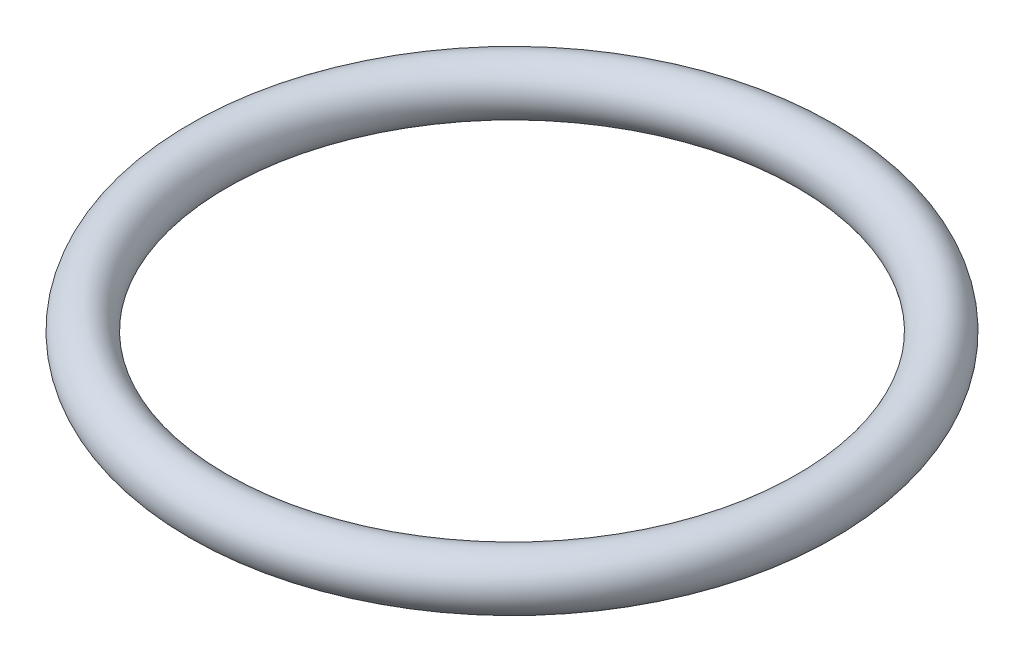
SolidWorks part; units mm, degrees
ref_plane "Front Plane" through (0, 0, 0) normal (0, 0, 1) x (1, 0, 0)
ref_plane "Top Plane" through (0, 0, 0) normal (0, 1, 0) x (1, 0, 0)
ref_plane "Right Plane" through (0, 0, 0) normal (1, 0, 0) x (0, 0, -1)
sketch "Sketch1" plane through (0, 0, 0) normal (0, 0, 1) x (1, 0, 0)
  line L0 (-27.7812, 0) -> (0, 0) construction
  line L1 (0, 0) -> (0, 8.4176) construction
  circle A0 centre (-27.7812, 0) radius 2.3813
  point P2 (-30.1625, 0)
  point P6 (-25.4, 0)
  dimension "D1" = 25.4
  dimension "D3" = 4.7625
  dimension "D2" = 30.1625
revolve "Revolve1" add sketch "Sketch1" angle 360 about L1
sketch "Sketch3" plane through (0, 0, 0) normal (0, 1, 0) x (1, 0, 0)
  line L0 (25.4, 0) -> (30.1625, 0) construction
  circle A0 centre (0, 0) radius 27.7813
  circle A1 centre (0, 0) radius 25.4 construction
  circle A2 centre (0, 0) radius 30.1625 construction
  point P9 (27.7812, 0)
  point P10 (0, 0)
